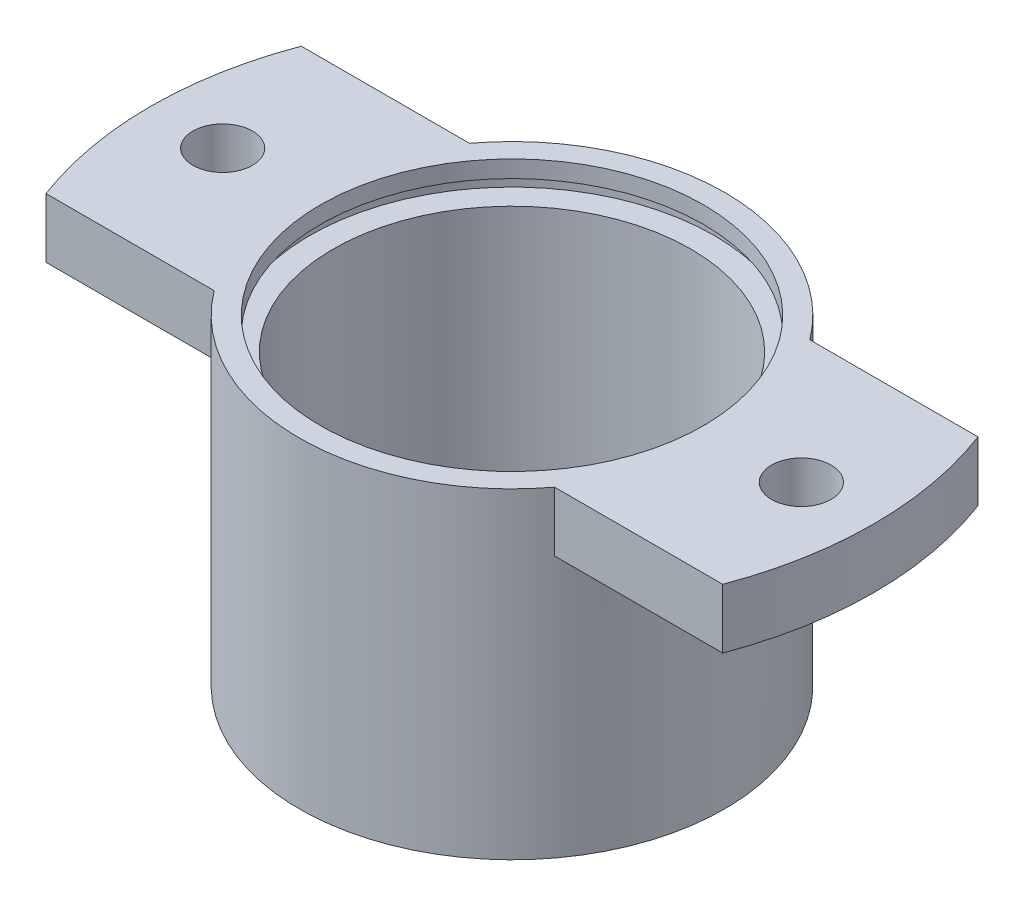
SolidWorks part; units mm, degrees
material "1060 合金"
ref_plane "Front Plane" through (0, 0, 0) normal (0, 0, 1) x (1, 0, 0)
ref_plane "Top Plane" through (0, 0, 0) normal (0, 1, 0) x (1, 0, 0)
ref_plane "Right Plane" through (0, 0, 0) normal (1, 0, 0) x (0, 0, -1)
sketch "Sketch4" plane through (0, 0, 0) normal (1, 0, 0) x (0, 0, -1)
  line L0 (0, 55) -> (0, -55) construction
  line L2 (-25, 37.75) -> (-25, 0)
  line L3 (55, 0) -> (-55, 0) construction
  line L4 (-25, 0) -> (-18, 0)
  line L5 (-18, 0) -> (-18, 2)
  line L6 (-18, 2) -> (-21, 2)
  line L7 (-21, 2) -> (-21, 34)
  line L8 (-21, 34) -> (-23.75, 34)
  line L9 (-23.75, 34) -> (-23.75, 35.75)
  line L10 (-23.75, 35.75) -> (-22.5, 35.75)
  line L11 (-22.5, 35.75) -> (-22.5, 37.75)
  line L12 (-22.5, 37.75) -> (-25, 37.75)
  line L13 (0, -1.1179) -> (0, 37.75) construction
  dimension "D1" = 2
  dimension "D2" = 32
  dimension "D3" = 1.75
  dimension "D4" = 2
  dimension "D5" = 21
  dimension "D6" = 4
  dimension "D7" = 7
  dimension "D8" = 23.75
  dimension "D9" = 22.5
revolve "Revolve1" add sketch "Sketch4" angle 360 about L13
sketch "Sketch5" plane through (0, 0, 0) normal (0, -1, 0) x (-1, 0, 0)
  line L0 (0, 22) -> (0, 0) construction
  line L1 (-5, 22) -> (5, 22)
  line L2 (-5, 22) -> (-5, 40)
  line L3 (-5, 40) -> (5, 40)
  line L4 (5, 22) -> (5, 40)
  circle A0 centre (0, 0) radius 18 construction
  dimension "D1" = 10
  dimension "D2" = 22
  dimension "D3" = 18
extrude "Boss-Extrude1" [suppressed] add sketch "Sketch5" against normal blind 37.75
sketch "Sketch6" [suppressed] plane through (-5, 0, 0) normal (-1, 0, 0) x (0, 0, 1)
  line L2 (-24.4949, 37.75) -> (-40, 37.75) construction
  line L3 (-40, 37.75) -> (-40, 0) construction
  circle A0 centre (-32.5, 28.95) radius 4
  circle A1 centre (-32.5, 8.95) radius 4
  dimension "D1" = 8
  dimension "D2" = 8
  dimension "D3" = 20
  dimension "D5" = 7.5
  dimension "D4" = 8.8
extrude "Cut-Extrude1" [suppressed] cut sketch "Sketch6" against normal blind 20
sketch "Sketch7" plane through (0, 37.75, 0) normal (0, 1, 0) x (1, 0, 0)
  line L0 (-39.7649, -15) -> (-20, -15)
  line L1 (39.7649, 15) -> (20, 15)
  line L2 (20, -15) -> (39.7649, -15)
  line L3 (-20, 15) -> (-39.7649, 15)
  arc A0 (-20, 15) -> (-20, -15) centre (0, 0) ccw
  arc A1 (39.7649, -15) -> (39.7649, 15) centre (0, 0) ccw
  circle A2 centre (0, 0) radius 21 construction
  circle A3 centre (0, 0) radius 21 construction
  arc A4 (-39.7649, 15) -> (-39.7649, -15) centre (0, 0) ccw
  arc A5 (20, -15) -> (20, 15) centre (0, 0) ccw
  dimension "D1" = 50
  dimension "D2" = 85
  dimension "D4" = 15
  dimension "D3" = 15
extrude "Boss-Extrude2" add sketch "Sketch7" against normal blind 7
sketch "Sketch8" plane through (0, 37.75, 0) normal (0, 1, 0) x (1, 0, 0)
  line L0 (-20.7625, 0) -> (20.7625, 0) construction
  circle A0 centre (34, 0) radius 3.5
  circle A1 centre (-34, 0) radius 3.5
  circle A2 centre (0, 0) radius 21 construction
  dimension "D1" = 7
  dimension "D2" = 7
  dimension "D3" = 34
  dimension "D4" = 34
extrude "Cut-Extrude2" cut sketch "Sketch8" against normal blind 7
